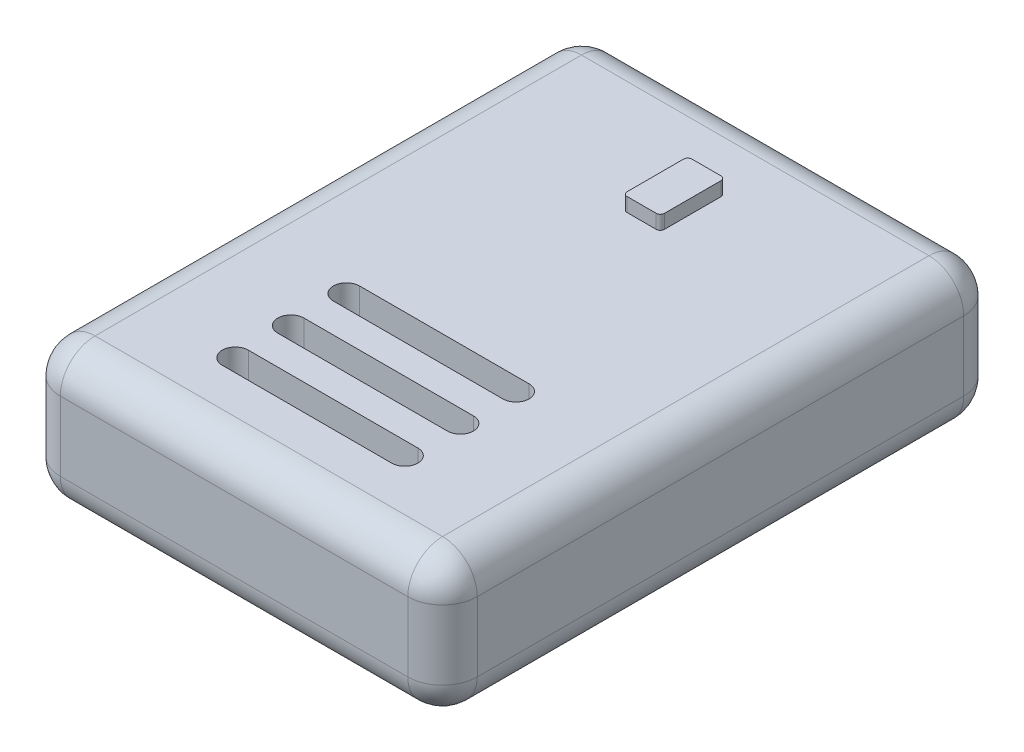
SolidWorks part; units mm, degrees
ref_plane "Front Plane" through (0, 0, 0) normal (0, 0, 1) x (1, 0, 0)
ref_plane "Top Plane" through (0, 0, 0) normal (0, 1, 0) x (1, 0, 0)
ref_plane "Right Plane" through (0, 0, 0) normal (1, 0, 0) x (0, 0, -1)
sketch "Sketch1" plane through (0, 0, 0) normal (0, 1, 0) x (1, 0, 0)
  line L1 (38.1, -50.8) -> (-38.1, -50.8)
  line L2 (38.1, -50.8) -> (38.1, 50.8)
  line L3 (38.1, 50.8) -> (-38.1, 50.8)
  line L4 (-38.1, -50.8) -> (-38.1, 50.8)
  line L5 (38.1, -50.8) -> (-38.1, 50.8) construction
  line L6 (38.1, 50.8) -> (-38.1, -50.8) construction
  point P0 (0, 0)
  dimension "D1" = 101.6
  dimension "D2" = 76.2
extrude "Boss-Extrude1" add sketch "Sketch1" along normal blind 25.4
fillet "Fillet1" radius 6.35 12 edges at (0, 0, 50.8) (38.1, 12.7, 50.8) (38.1, 0, 0) (38.1, 12.7, -50.8) (0, 0, -50.8) (-38.1, 12.7, -50.8) (-38.1, 12.7, 50.8) (-38.1, 0, 0) (0, 25.4, -50.8) (38.1, 25.4, 0) (0, 25.4, 50.8) (-38.1, 25.4, 0)
sketch "Sketch3" plane through (0, 25.4, 0) normal (0, 1, 0) x (1, 0, 0)
  line L0 (0, -44.45) -> (0, 0) construction
  line L1 (-31.75, -44.45) -> (31.75, -44.45) construction
  line L2 (15.4912, -35.083) -> (-15.4912, -35.083) construction
  line L3 (15.4912, -37.475) -> (-15.4912, -37.475)
  line L4 (15.4912, -32.691) -> (-15.4912, -32.691)
  line L5 (15.4912, -24.923) -> (-15.4912, -24.923) construction
  line L6 (15.4912, -27.315) -> (-15.4912, -27.315)
  line L7 (15.4912, -22.531) -> (-15.4912, -22.531)
  line L8 (15.4912, -14.763) -> (-15.4912, -14.763) construction
  line L9 (15.4912, -17.155) -> (-15.4912, -17.155)
  line L10 (15.4912, -12.371) -> (-15.4912, -12.371)
  arc A0 (15.4912, -37.475) -> (15.4912, -32.691) centre (15.4912, -35.083) ccw
  arc A1 (-15.4912, -32.691) -> (-15.4912, -37.475) centre (-15.4912, -35.083) ccw
  arc A2 (15.4912, -27.315) -> (15.4912, -22.531) centre (15.4912, -24.923) ccw
  arc A3 (-15.4912, -22.531) -> (-15.4912, -27.315) centre (-15.4912, -24.923) ccw
  arc A4 (15.4912, -17.155) -> (15.4912, -12.371) centre (15.4912, -14.763) ccw
  arc A5 (-15.4912, -12.371) -> (-15.4912, -17.155) centre (-15.4912, -14.763) ccw
  point P7 (0, -35.083)
  point P15 (0, -24.923)
  point P22 (0, -14.763)
  dimension "D1" = 3
extrude "Cut-Extrude1" cut sketch "Sketch3" against normal blind 6.35
sketch "Sketch4" plane through (0, 25.4, 0) normal (0, 1, 0) x (1, 0, 0)
  line L0 (0, 0) -> (0, 44.45) construction
  line L1 (31.75, 44.45) -> (-31.75, 44.45) construction
  line L3 (3.4172, 35.5386) -> (-3.4172, 35.5386)
  line L4 (3.4172, 35.5386) -> (3.4172, 23.6924)
  line L5 (3.4172, 23.6924) -> (-3.4172, 23.6924)
  line L6 (-3.4172, 35.5386) -> (-3.4172, 23.6924)
  line L7 (3.4172, 35.5386) -> (-3.4172, 23.6924) construction
  line L8 (3.4172, 23.6924) -> (-3.4172, 35.5386) construction
  point P5 (0, 29.6155)
extrude "Boss-Extrude2" add sketch "Sketch4" along normal blind 2.54
fillet "Fillet2" radius 0.762 4 edges at (3.4172, 26.67, -35.5386) (-3.4172, 26.67, -35.5386) (-3.4172, 26.67, -23.6924) (3.4172, 26.67, -23.6924)
